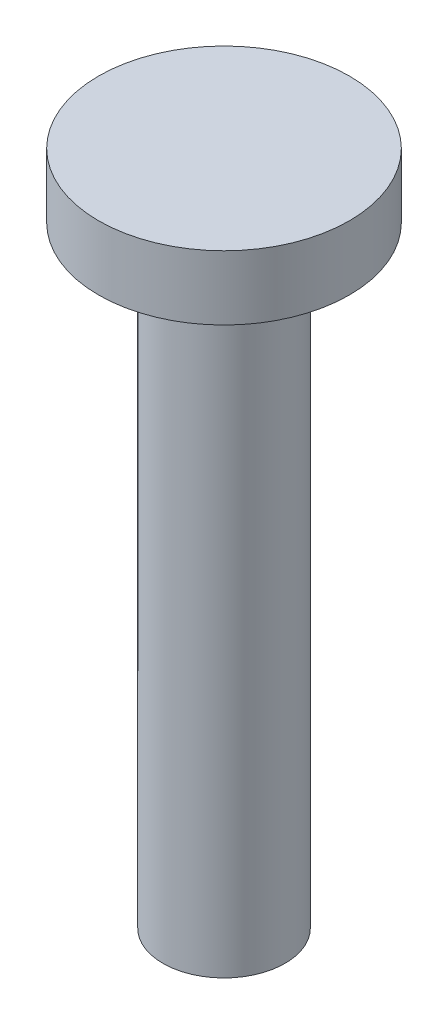
SolidWorks part; units mm, degrees
ref_plane "Front Plane" through (0, 0, 0) normal (0, 0, 1) x (1, 0, 0)
ref_plane "Top Plane" through (0, 0, 0) normal (0, 1, 0) x (1, 0, 0)
ref_plane "Right Plane" through (0, 0, 0) normal (1, 0, 0) x (0, 0, -1)
sketch "Sketch2" plane through (0, 0, 0) normal (0, 0, 1) x (1, 0, 0)
  line L0 (0, 0) -> (0, 19)
  line L1 (0, 19) -> (-2, 19)
  line L2 (-2, 19) -> (-2, 21)
  line L3 (-2, 21) -> (1.9, 21)
  line L4 (1.9, 21) -> (1.9, 0)
  line L5 (1.9, 0) -> (0, 0)
  dimension "D1" = 1.9
  dimension "D2" = 2
  dimension "D3" = 2
  dimension "D4" = 19
revolve "Revolve1" add sketch "Sketch2" angle 360 about L4
